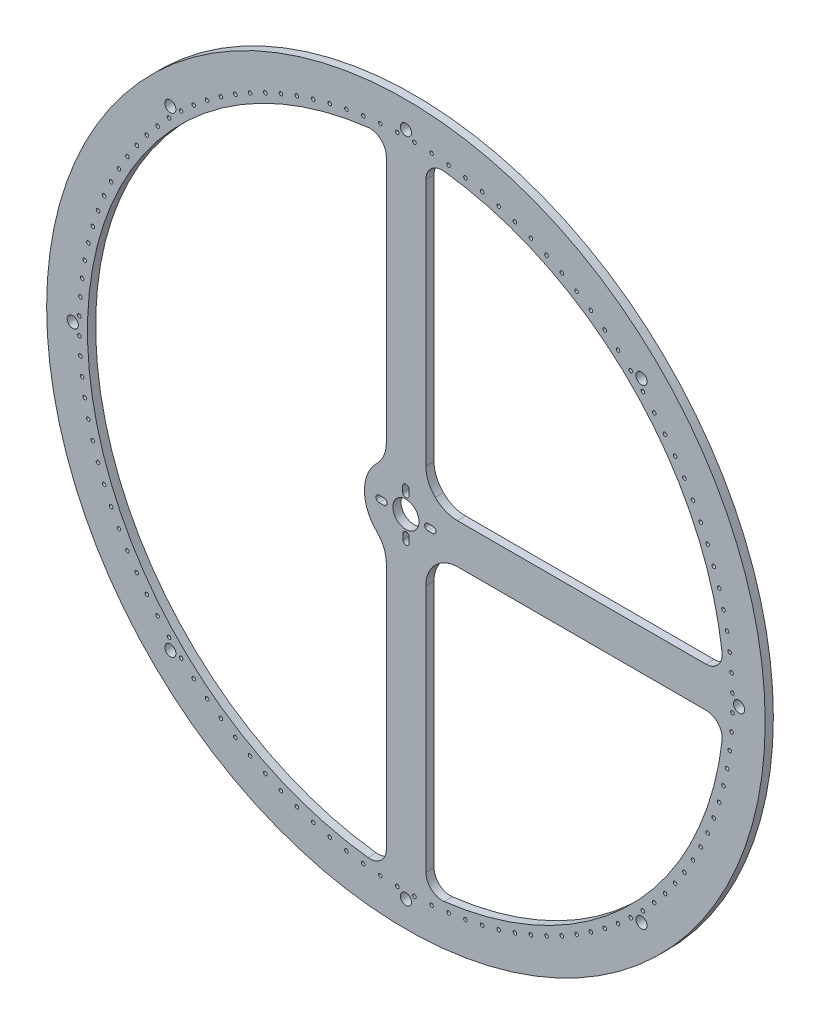
SolidWorks part; units mm, degrees
ref_plane "Front Plane" through (0, 0, 0) normal (0, 0, 1) x (1, 0, 0)
ref_plane "Top Plane" through (0, 0, 0) normal (0, 1, 0) x (1, 0, 0)
ref_plane "Right Plane" through (0, 0, 0) normal (1, 0, 0) x (0, 0, -1)
sketch "Sketch1" plane through (0, 0, 0) normal (0, 0, 1) x (1, 0, 0)
  line L1 (175.6086, 1.25) -> (173.6914, 1.25)
  line L2 (173.6914, -1.25) -> (175.6086, -1.25)
  line L3 (182.9414, -7.079) -> (182.9414, -9.079)
  line L4 (185.4414, -7.079) -> (185.4414, -9.079) construction
  line L5 (194.6086, -1.25) -> (192.6914, -1.25)
  line L6 (192.6914, 1.25) -> (194.6086, 1.25)
  line L7 (185.4, 6.921) -> (185.4, 8.9209)
  line L8 (182.9, 8.9209) -> (182.9, 6.921)
  line L9 (182.9414, -7.079) -> (182.9414, -9.079)
  line L10 (185.4414, -9.079) -> (185.4414, -7.079)
  line L15 (191.9159, -0.9804) -> (191.9159, 0.9804)
  line L20 (54.61, 0) -> (60.325, 0)
  line L21 (57.1935, -3.3245) -> (60.3674, -3.2414)
  line L28 (176.53, -20.257) -> (176.53, -116.6414)
  line L29 (204.407, -7.62) -> (300.7914, -7.62)
  line L30 (300.7587, 7.8903) -> (204.1386, 7.8903)
  line L31 (191.9159, 20.113) -> (191.9159, 116.6238)
  line L32 (176.53, 116.6414) -> (176.53, 20.257)
  line L33 (191.9159, -20.113) -> (191.9159, -116.6238)
  arc A0 (169.4249, 122.9463) -> (169.4249, -122.9463) centre (184.15, 0) ccw
  arc A9 (173.6914, -1.25) -> (173.6914, 1.25) centre (173.6914, 0) cw
  arc A10 (173.6914, 1.25) -> (173.6914, -1.25) centre (173.6914, 0) ccw construction
  arc A11 (175.6086, -1.25) -> (175.6086, 1.25) centre (175.6086, 0) ccw
  arc A12 (175.6086, -1.25) -> (175.6086, 1.25) centre (175.6086, 0) ccw construction
  arc A13 (182.9414, -9.079) -> (185.4414, -9.079) centre (184.1914, -9.079) ccw
  arc A14 (185.4414, -7.079) -> (182.9414, -7.079) centre (184.1914, -7.079) ccw
  arc A15 (185.4414, -7.079) -> (182.9414, -7.079) centre (184.1914, -7.079) ccw construction
  arc A16 (182.9, 6.921) -> (185.4, 6.921) centre (184.15, 6.921) ccw
  arc A17 (182.9, 6.921) -> (185.4, 6.921) centre (184.15, 6.921) ccw construction
  arc A18 (185.4, 8.9209) -> (182.9, 8.9209) centre (184.15, 8.9209) ccw
  arc A19 (185.4, 8.9209) -> (182.9, 8.9209) centre (184.15, 8.9209) ccw construction
  arc A20 (194.6086, -1.25) -> (194.6086, 1.25) centre (194.6086, 0) ccw
  arc A21 (194.6086, -1.25) -> (194.6086, 1.25) centre (194.6086, 0) ccw construction
  arc A22 (192.6914, -1.25) -> (192.6914, 1.25) centre (192.6914, 0) cw
  arc A23 (192.6914, 1.25) -> (192.6914, -1.25) centre (192.6914, 0) ccw construction
  circle A26 centre (313.69, 0) radius 2.159
  circle A27 centre (313.69, 0) radius 2.159
  circle A30 centre (184.15, -129.54) radius 2.159
  circle A33 centre (54.61, 0) radius 2.159
  circle A36 centre (184.15, 129.54) radius 2.159
  circle A39 centre (57.1935, -3.3245) radius 0.6985
  circle A40 centre (184.15, 0) radius 5.08 construction
  circle A41 centre (57.1935, 3.3245) radius 0.6985
  circle A42 centre (57.5415, 9.9643) radius 0.6985
  circle A43 centre (58.2365, 16.5768) radius 0.6985
  circle A44 centre (59.2766, 23.1439) radius 0.6985
  circle A45 centre (60.659, 29.6476) radius 0.6985
  circle A46 centre (62.3799, 36.0699) radius 0.6985
  circle A47 centre (64.4345, 42.3935) radius 0.6985
  circle A48 centre (66.8173, 48.6008) radius 0.6985
  circle A49 centre (69.5217, 54.6749) radius 0.6985
  circle A50 centre (72.5402, 60.5992) radius 0.6985
  circle A51 centre (75.8647, 66.3573) radius 0.6985
  circle A52 centre (79.486, 71.9336) radius 0.6985
  circle A53 centre (83.3941, 77.3127) radius 0.6985
  circle A54 centre (87.5784, 82.4799) radius 0.6985
  circle A55 centre (92.0275, 87.421) radius 0.6985
  circle A56 centre (96.729, 92.1225) radius 0.6985
  circle A57 centre (101.6701, 96.5716) radius 0.6985
  circle A58 centre (106.8373, 100.7559) radius 0.6985
  circle A59 centre (112.2164, 104.664) radius 0.6985
  circle A60 centre (117.7927, 108.2853) radius 0.6985
  circle A61 centre (123.5508, 111.6098) radius 0.6985
  circle A62 centre (129.4751, 114.6283) radius 0.6985
  circle A63 centre (135.5492, 117.3327) radius 0.6985
  circle A64 centre (141.7565, 119.7155) radius 0.6985
  circle A65 centre (148.0801, 121.7701) radius 0.6985
  circle A66 centre (154.5024, 123.491) radius 0.6985
  circle A67 centre (161.0061, 124.8734) radius 0.6985
  circle A68 centre (167.5732, 125.9135) radius 0.6985
  circle A69 centre (174.1857, 126.6085) radius 0.6985
  circle A70 centre (180.8255, 126.9565) radius 0.6985
  circle A71 centre (187.4745, 126.9565) radius 0.6985
  circle A72 centre (194.1143, 126.6085) radius 0.6985
  circle A73 centre (200.7268, 125.9135) radius 0.6985
  circle A74 centre (207.2939, 124.8734) radius 0.6985
  circle A75 centre (213.7976, 123.491) radius 0.6985
  circle A76 centre (220.2199, 121.7701) radius 0.6985
  circle A77 centre (226.5435, 119.7155) radius 0.6985
  circle A78 centre (232.7508, 117.3327) radius 0.6985
  circle A79 centre (238.8249, 114.6283) radius 0.6985
  circle A80 centre (244.7492, 111.6098) radius 0.6985
  circle A81 centre (250.5073, 108.2853) radius 0.6985
  circle A82 centre (256.0836, 104.664) radius 0.6985
  circle A83 centre (261.4627, 100.7559) radius 0.6985
  circle A84 centre (266.6299, 96.5716) radius 0.6985
  circle A85 centre (271.571, 92.1225) radius 0.6985
  circle A86 centre (276.2725, 87.421) radius 0.6985
  circle A87 centre (280.7216, 82.4799) radius 0.6985
  circle A88 centre (284.9059, 77.3127) radius 0.6985
  circle A89 centre (288.814, 71.9336) radius 0.6985
  circle A90 centre (292.4353, 66.3573) radius 0.6985
  circle A91 centre (295.7598, 60.5992) radius 0.6985
  circle A92 centre (298.7783, 54.6749) radius 0.6985
  circle A93 centre (301.4827, 48.6008) radius 0.6985
  circle A94 centre (303.8655, 42.3935) radius 0.6985
  circle A95 centre (305.9201, 36.0699) radius 0.6985
  circle A96 centre (307.641, 29.6476) radius 0.6985
  circle A97 centre (309.0234, 23.1439) radius 0.6985
  circle A98 centre (310.0635, 16.5768) radius 0.6985
  circle A99 centre (310.7585, 9.9643) radius 0.6985
  circle A100 centre (311.1065, 3.3245) radius 0.6985
  circle A101 centre (311.1065, -3.3245) radius 0.6985
  circle A102 centre (310.7585, -9.9643) radius 0.6985
  circle A103 centre (310.0635, -16.5768) radius 0.6985
  circle A104 centre (309.0234, -23.1439) radius 0.6985
  circle A105 centre (307.641, -29.6476) radius 0.6985
  circle A106 centre (305.9201, -36.0699) radius 0.6985
  circle A107 centre (303.8655, -42.3935) radius 0.6985
  circle A108 centre (301.4827, -48.6008) radius 0.6985
  circle A109 centre (298.7783, -54.6749) radius 0.6985
  circle A110 centre (295.7598, -60.5992) radius 0.6985
  circle A111 centre (292.4353, -66.3573) radius 0.6985
  circle A112 centre (288.814, -71.9336) radius 0.6985
  circle A113 centre (284.9059, -77.3127) radius 0.6985
  circle A114 centre (280.7216, -82.4799) radius 0.6985
  circle A115 centre (276.2725, -87.421) radius 0.6985
  circle A116 centre (271.571, -92.1225) radius 0.6985
  circle A117 centre (266.6299, -96.5716) radius 0.6985
  circle A118 centre (261.4627, -100.7559) radius 0.6985
  circle A119 centre (256.0836, -104.664) radius 0.6985
  circle A120 centre (250.5073, -108.2853) radius 0.6985
  circle A121 centre (244.7492, -111.6098) radius 0.6985
  circle A122 centre (238.8249, -114.6283) radius 0.6985
  circle A123 centre (232.7508, -117.3327) radius 0.6985
  circle A124 centre (226.5435, -119.7155) radius 0.6985
  circle A125 centre (220.2199, -121.7701) radius 0.6985
  circle A126 centre (213.7976, -123.491) radius 0.6985
  circle A127 centre (207.2939, -124.8734) radius 0.6985
  circle A128 centre (200.7268, -125.9135) radius 0.6985
  circle A129 centre (194.1143, -126.6085) radius 0.6985
  circle A130 centre (187.4745, -126.9565) radius 0.6985
  circle A131 centre (180.8255, -126.9565) radius 0.6985
  circle A132 centre (174.1857, -126.6085) radius 0.6985
  circle A133 centre (167.5732, -125.9135) radius 0.6985
  circle A134 centre (161.0061, -124.8734) radius 0.6985
  circle A135 centre (154.5024, -123.491) radius 0.6985
  circle A136 centre (148.0801, -121.7701) radius 0.6985
  circle A137 centre (141.7565, -119.7155) radius 0.6985
  circle A138 centre (135.5492, -117.3327) radius 0.6985
  circle A139 centre (129.4751, -114.6283) radius 0.6985
  circle A140 centre (123.5508, -111.6098) radius 0.6985
  circle A141 centre (117.7927, -108.2853) radius 0.6985
  circle A142 centre (112.2164, -104.664) radius 0.6985
  circle A143 centre (106.8373, -100.7559) radius 0.6985
  circle A144 centre (101.6701, -96.5716) radius 0.6985
  circle A145 centre (96.729, -92.1225) radius 0.6985
  circle A146 centre (92.0275, -87.421) radius 0.6985
  circle A147 centre (87.5784, -82.4799) radius 0.6985
  circle A148 centre (83.3941, -77.3127) radius 0.6985
  circle A149 centre (79.486, -71.9336) radius 0.6985
  circle A150 centre (75.8647, -66.3573) radius 0.6985
  circle A151 centre (72.5402, -60.5992) radius 0.6985
  circle A152 centre (69.5217, -54.6749) radius 0.6985
  circle A153 centre (66.8173, -48.6008) radius 0.6985
  circle A154 centre (64.4345, -42.3935) radius 0.6985
  circle A155 centre (62.3799, -36.0699) radius 0.6985
  circle A156 centre (60.659, -29.6476) radius 0.6985
  circle A157 centre (59.2766, -23.1439) radius 0.6985
  circle A158 centre (58.2365, -16.5768) radius 0.6985
  circle A159 centre (57.5415, -9.9643) radius 0.6985
  circle A165 centre (184.15, 0) radius 5.08
  arc A166 (199.029, -122.9278) -> (307.0963, -14.7251) centre (184.15, 0) ccw
  arc A167 (307.0619, 15.01) -> (199.029, 122.9278) centre (184.15, 0) ccw
  arc A168 (199.029, -122.9278) -> (191.9159, -116.6238) centre (198.2659, -116.6238) cw
  arc A169 (169.4249, -122.9463) -> (176.53, -116.6414) centre (170.18, -116.6414) ccw
  arc A170 (176.53, 116.6414) -> (169.4249, 122.9463) centre (170.18, 116.6414) ccw
  arc A171 (199.029, 122.9278) -> (191.9159, 116.6238) centre (198.2659, 116.6238) ccw
  arc A172 (307.0963, -14.7251) -> (300.7914, -7.62) centre (300.7914, -13.97) ccw
  arc A173 (307.0619, 15.01) -> (300.7587, 7.8903) centre (300.7587, 14.2403) cw
  arc A174 (172.8603, 11.5255) -> (172.8603, -11.5255) centre (184.15, 0) ccw
  arc A175 (195.5228, 11.4435) -> (195.5227, 11.4436) centre (184.15, 0) ccw
  arc A176 (195.5227, -11.4436) -> (195.6755, -11.2897) centre (184.15, 0) ccw
  arc A177 (176.53, 20.257) -> (172.8603, 11.5255) centre (164.3075, 20.257) cw
  arc A178 (176.53, -20.257) -> (172.8603, -11.5255) centre (164.3075, -20.257) ccw
  arc A179 (195.5227, -11.4436) -> (191.9159, -20.113) centre (204.1384, -20.113) ccw
  arc A180 (204.407, -7.62) -> (195.6755, -11.2897) centre (204.407, -19.8425) ccw
  arc A181 (195.5228, 11.4435) -> (204.1386, 7.8903) centre (204.1386, 20.1128) ccw
  arc A182 (195.5227, 11.4436) -> (191.9159, 20.113) centre (204.1384, 20.113) cw
  circle A183 centre (248.92, -112.1849) radius 2.159 [skipped]
  circle A184 centre (119.38, -112.1849) radius 2.159 [skipped]
  circle A185 centre (71.9651, -64.77) radius 2.159 [skipped]
  circle A186 centre (71.9651, 64.77) radius 2.159 [skipped]
  circle A187 centre (119.38, 112.1849) radius 2.159 [skipped]
  circle A188 centre (296.3349, 64.77) radius 2.159 [skipped]
  circle A189 centre (296.3349, -64.77) radius 2.159 [skipped]
  circle A190 centre (248.92, 112.1849) radius 2.159 [skipped]
  circle A191 centre (184.15, 0) radius 139.7
  point P106 (184.15, 0)
  point P357 (184.15, 0)
  point P364 (307.7403, -7.62)
  point P367 (307.7234, 7.8903)
  point P372 (191.9159, -14.1416)
  point P377 (198.2226, 7.8903)
  dimension "D1" = 247.65
  dimension "D7" = 4.318
  dimension "D9" = 12
  dimension "D10" = 1.397
  dimension "D11" = 127
  dimension "D3" = 6.35
  dimension "D4" = 12.2225
  dimension "D5" = 279.4
  dimension "D8" = 129.54
  dimension "D12" = 1.5
  dimension "D13" = 120
extrude "Boss-Extrude1" add sketch "Sketch1" along normal blind 3.175 contours A191 A159 A158 A157 A156 A155 A154 A153 A152 A151 A150 A149 A148 A147 A146 A145 A144 A143 A142 A141 A140 A139 A138 A137 A136 A135
sketch "Sketch2" plane through (0, 0, 0) normal (0, 0, -1) x (-1, 0, 0)
  line L0 (-92.5514, -91.5986) -> (-184.15, 0)
  line L1 (-184.15, 0) -> (-184.15, -129.54)
  circle A0 centre (-92.5514, -91.5986) radius 2.159
  circle A1 centre (-275.7486, -91.5986) radius 2.159
  circle A2 centre (-275.7486, 91.5986) radius 2.159
  circle A3 centre (-92.5514, 91.5986) radius 2.159
  point P15 (-184.15, 0)
  dimension "D3" = 4.318
  dimension "D1" = 129.54
  dimension "D2" = 45
  dimension "D4" = 4
extrude "Cut-Extrude1" cut sketch "Sketch2" against normal through all both and the other way through all
